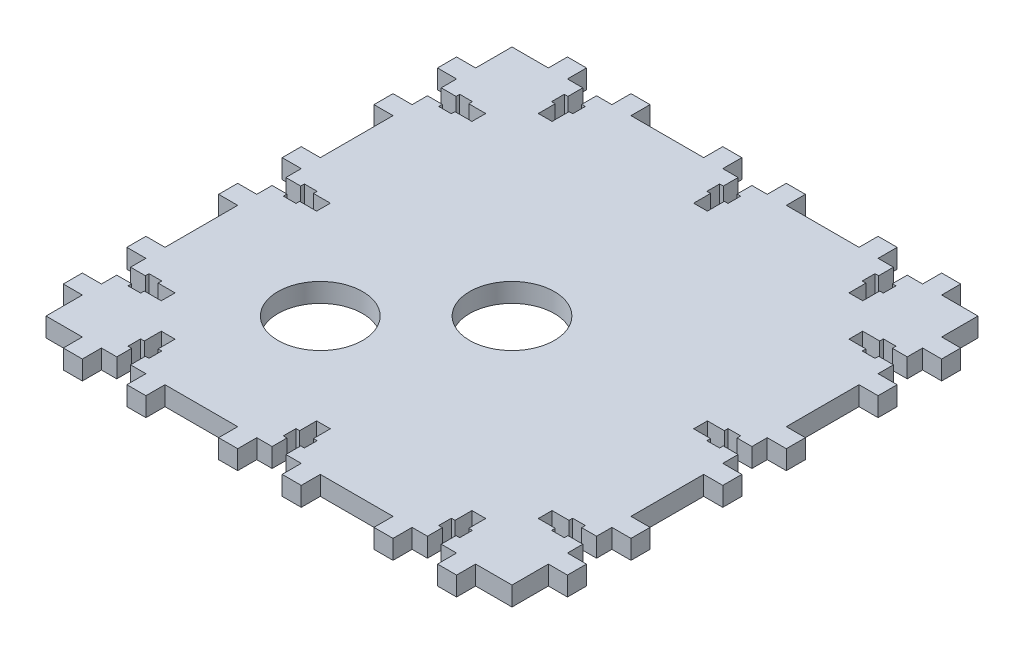
SolidWorks part; units mm, degrees
ref_plane "Front Plane" through (0, 0, 0) normal (0, 0, 1) x (1, 0, 0)
ref_plane "Top Plane" through (0, 0, 0) normal (0, 1, 0) x (1, 0, 0)
ref_plane "Right Plane" through (0, 0, 0) normal (1, 0, 0) x (0, 0, -1)
sketch "Sketch1" plane through (0, 0, 0) normal (0, 1, 0) x (1, 0, 0)
  line L0 (0, 0) -> (0, -110) construction
  line L1 (-110, -110) -> (110, -110)
  line L2 (-110, -110) -> (-110, 110)
  line L3 (-110, 110) -> (110, 110)
  line L4 (110, -110) -> (110, 110)
  line L5 (-110, -110) -> (110, 110) construction
  line L6 (-110, 110) -> (110, -110) construction
  line L7 (0, 0) -> (110, 0) construction
  line L8 (110, -32) -> (-110, -32) construction
  line L9 (-110, 72.5) -> (110, 72.5) construction
  circle A0 centre (0, 0) radius 20
  circle A6 centre (-45.2548, -45.2548) radius 20
  point P0 (0, 0)
  point P28 (0, 0)
  line B0 (-92.8333, -110) -> (-92.8333, -119)
  line B1 (-92.8333, -119) -> (-83.8333, -119)
  line B2 (-83.8333, -119) -> (-83.8333, -110)
  line B3 (-83.8333, -110) -> (-76.5833, -110)
  line B4 (-76.5833, -110) -> (-76.5833, -103)
  line B5 (-76.5833, -103) -> (-78.3083, -103)
  line B6 (-78.3083, -103) -> (-78.3083, -97)
  line B7 (-78.3083, -97) -> (-76.5833, -97)
  line B8 (-76.5833, -97) -> (-76.5833, -89)
  line B9 (-76.5833, -89) -> (-70.0833, -89)
  line B10 (-73.3333, -89) -> (-73.3333, -110) construction
  line B11 (-70.0833, -97) -> (-70.0833, -89)
  line B12 (-68.3583, -97) -> (-70.0833, -97)
  line B13 (-68.3583, -103) -> (-68.3583, -97)
  line B14 (-70.0833, -103) -> (-68.3583, -103)
  line B15 (-70.0833, -110) -> (-70.0833, -103)
  line B16 (-62.8333, -110) -> (-70.0833, -110)
  line B17 (-62.8333, -119) -> (-62.8333, -110)
  line B18 (-53.8333, -119) -> (-62.8333, -119)
  line B19 (-53.8333, -110) -> (-53.8333, -119)
  line B20 (-19.5, -110) -> (-19.5, -119)
  line B21 (-19.5, -119) -> (-10.5, -119)
  line B22 (-10.5, -119) -> (-10.5, -110)
  line B23 (-10.5, -110) -> (-3.25, -110)
  line B24 (-3.25, -110) -> (-3.25, -103)
  line B25 (-3.25, -103) -> (-4.975, -103)
  line B26 (-4.975, -103) -> (-4.975, -97)
  line B27 (-4.975, -97) -> (-3.25, -97)
  line B28 (-3.25, -97) -> (-3.25, -89)
  line B29 (-3.25, -89) -> (3.25, -89)
  line B30 (0, -89) -> (0, -110) construction
  line B31 (3.25, -97) -> (3.25, -89)
  line B32 (4.975, -97) -> (3.25, -97)
  line B33 (4.975, -103) -> (4.975, -97)
  line B34 (3.25, -103) -> (4.975, -103)
  line B35 (3.25, -110) -> (3.25, -103)
  line B36 (10.5, -110) -> (3.25, -110)
  line B37 (10.5, -119) -> (10.5, -110)
  line B38 (19.5, -119) -> (10.5, -119)
  line B39 (19.5, -110) -> (19.5, -119)
  line B40 (53.8333, -110) -> (53.8333, -119)
  line B41 (53.8333, -119) -> (62.8333, -119)
  line B42 (62.8333, -119) -> (62.8333, -110)
  line B43 (62.8333, -110) -> (70.0833, -110)
  line B44 (70.0833, -110) -> (70.0833, -103)
  line B45 (70.0833, -103) -> (68.3583, -103)
  line B46 (68.3583, -103) -> (68.3583, -97)
  line B47 (68.3583, -97) -> (70.0833, -97)
  line B48 (70.0833, -97) -> (70.0833, -89)
  line B49 (70.0833, -89) -> (76.5833, -89)
  line B50 (73.3333, -89) -> (73.3333, -110) construction
  line B51 (76.5833, -97) -> (76.5833, -89)
  line B52 (78.3083, -97) -> (76.5833, -97)
  line B53 (78.3083, -103) -> (78.3083, -97)
  line B54 (76.5833, -103) -> (78.3083, -103)
  line B55 (76.5833, -110) -> (76.5833, -103)
  line B56 (83.8333, -110) -> (76.5833, -110)
  line B57 (83.8333, -119) -> (83.8333, -110)
  line B58 (92.8333, -119) -> (83.8333, -119)
  line B59 (92.8333, -110) -> (92.8333, -119)
  line B60 (-110, 92.8333) -> (-119, 92.8333)
  line B61 (-119, 92.8333) -> (-119, 83.8333)
  line B62 (-119, 83.8333) -> (-110, 83.8333)
  line B63 (-110, 83.8333) -> (-110, 76.5833)
  line B64 (-110, 76.5833) -> (-103, 76.5833)
  line B65 (-103, 76.5833) -> (-103, 78.3083)
  line B66 (-103, 78.3083) -> (-97, 78.3083)
  line B67 (-97, 78.3083) -> (-97, 76.5833)
  line B68 (-97, 76.5833) -> (-89, 76.5833)
  line B69 (-89, 76.5833) -> (-89, 70.0833)
  line B70 (-89, 73.3333) -> (-110, 73.3333) construction
  line B71 (-97, 70.0833) -> (-89, 70.0833)
  line B72 (-97, 68.3583) -> (-97, 70.0833)
  line B73 (-103, 68.3583) -> (-97, 68.3583)
  line B74 (-103, 70.0833) -> (-103, 68.3583)
  line B75 (-110, 70.0833) -> (-103, 70.0833)
  line B76 (-110, 62.8333) -> (-110, 70.0833)
  line B77 (-119, 62.8333) -> (-110, 62.8333)
  line B78 (-119, 53.8333) -> (-119, 62.8333)
  line B79 (-110, 53.8333) -> (-119, 53.8333)
  line B80 (-110, 19.5) -> (-119, 19.5)
  line B81 (-119, 19.5) -> (-119, 10.5)
  line B82 (-119, 10.5) -> (-110, 10.5)
  line B83 (-110, 10.5) -> (-110, 3.25)
  line B84 (-110, 3.25) -> (-103, 3.25)
  line B85 (-103, 3.25) -> (-103, 4.975)
  line B86 (-103, 4.975) -> (-97, 4.975)
  line B87 (-97, 4.975) -> (-97, 3.25)
  line B88 (-97, 3.25) -> (-89, 3.25)
  line B89 (-89, 3.25) -> (-89, -3.25)
  line B90 (-89, 0) -> (-110, 0) construction
  line B91 (-97, -3.25) -> (-89, -3.25)
  line B92 (-97, -4.975) -> (-97, -3.25)
  line B93 (-103, -4.975) -> (-97, -4.975)
  line B94 (-103, -3.25) -> (-103, -4.975)
  line B95 (-110, -3.25) -> (-103, -3.25)
  line B96 (-110, -10.5) -> (-110, -3.25)
  line B97 (-119, -10.5) -> (-110, -10.5)
  line B98 (-119, -19.5) -> (-119, -10.5)
  line B99 (-110, -19.5) -> (-119, -19.5)
  line B100 (-110, -53.8333) -> (-119, -53.8333)
  line B101 (-119, -53.8333) -> (-119, -62.8333)
  line B102 (-119, -62.8333) -> (-110, -62.8333)
  line B103 (-110, -62.8333) -> (-110, -70.0833)
  line B104 (-110, -70.0833) -> (-103, -70.0833)
  line B105 (-103, -70.0833) -> (-103, -68.3583)
  line B106 (-103, -68.3583) -> (-97, -68.3583)
  line B107 (-97, -68.3583) -> (-97, -70.0833)
  line B108 (-97, -70.0833) -> (-89, -70.0833)
  line B109 (-89, -70.0833) -> (-89, -76.5833)
  line B110 (-89, -73.3333) -> (-110, -73.3333) construction
  line B111 (-97, -76.5833) -> (-89, -76.5833)
  line B112 (-97, -78.3083) -> (-97, -76.5833)
  line B113 (-103, -78.3083) -> (-97, -78.3083)
  line B114 (-103, -76.5833) -> (-103, -78.3083)
  line B115 (-110, -76.5833) -> (-103, -76.5833)
  line B116 (-110, -83.8333) -> (-110, -76.5833)
  line B117 (-119, -83.8333) -> (-110, -83.8333)
  line B118 (-119, -92.8333) -> (-119, -83.8333)
  line B119 (-110, -92.8333) -> (-119, -92.8333)
  line B120 (92.8333, 110) -> (92.8333, 119)
  line B121 (92.8333, 119) -> (83.8333, 119)
  line B122 (83.8333, 119) -> (83.8333, 110)
  line B123 (83.8333, 110) -> (76.5833, 110)
  line B124 (76.5833, 110) -> (76.5833, 103)
  line B125 (76.5833, 103) -> (78.3083, 103)
  line B126 (78.3083, 103) -> (78.3083, 97)
  line B127 (78.3083, 97) -> (76.5833, 97)
  line B128 (76.5833, 97) -> (76.5833, 89)
  line B129 (76.5833, 89) -> (70.0833, 89)
  line B130 (73.3333, 89) -> (73.3333, 110) construction
  line B131 (70.0833, 97) -> (70.0833, 89)
  line B132 (68.3583, 97) -> (70.0833, 97)
  line B133 (68.3583, 103) -> (68.3583, 97)
  line B134 (70.0833, 103) -> (68.3583, 103)
  line B135 (70.0833, 110) -> (70.0833, 103)
  line B136 (62.8333, 110) -> (70.0833, 110)
  line B137 (62.8333, 119) -> (62.8333, 110)
  line B138 (53.8333, 119) -> (62.8333, 119)
  line B139 (53.8333, 110) -> (53.8333, 119)
  line B140 (19.5, 110) -> (19.5, 119)
  line B141 (19.5, 119) -> (10.5, 119)
  line B142 (10.5, 119) -> (10.5, 110)
  line B143 (10.5, 110) -> (3.25, 110)
  line B144 (3.25, 110) -> (3.25, 103)
  line B145 (3.25, 103) -> (4.975, 103)
  line B146 (4.975, 103) -> (4.975, 97)
  line B147 (4.975, 97) -> (3.25, 97)
  line B148 (3.25, 97) -> (3.25, 89)
  line B149 (3.25, 89) -> (-3.25, 89)
  line B150 (0, 89) -> (0, 110) construction
  line B151 (-3.25, 97) -> (-3.25, 89)
  line B152 (-4.975, 97) -> (-3.25, 97)
  line B153 (-4.975, 103) -> (-4.975, 97)
  line B154 (-3.25, 103) -> (-4.975, 103)
  line B155 (-3.25, 110) -> (-3.25, 103)
  line B156 (-10.5, 110) -> (-3.25, 110)
  line B157 (-10.5, 119) -> (-10.5, 110)
  line B158 (-19.5, 119) -> (-10.5, 119)
  line B159 (-19.5, 110) -> (-19.5, 119)
  line B160 (-53.8333, 110) -> (-53.8333, 119)
  line B161 (-53.8333, 119) -> (-62.8333, 119)
  line B162 (-62.8333, 119) -> (-62.8333, 110)
  line B163 (-62.8333, 110) -> (-70.0833, 110)
  line B164 (-70.0833, 110) -> (-70.0833, 103)
  line B165 (-70.0833, 103) -> (-68.3583, 103)
  line B166 (-68.3583, 103) -> (-68.3583, 97)
  line B167 (-68.3583, 97) -> (-70.0833, 97)
  line B168 (-70.0833, 97) -> (-70.0833, 89)
  line B169 (-70.0833, 89) -> (-76.5833, 89)
  line B170 (-73.3333, 89) -> (-73.3333, 110) construction
  line B171 (-76.5833, 97) -> (-76.5833, 89)
  line B172 (-78.3083, 97) -> (-76.5833, 97)
  line B173 (-78.3083, 103) -> (-78.3083, 97)
  line B174 (-76.5833, 103) -> (-78.3083, 103)
  line B175 (-76.5833, 110) -> (-76.5833, 103)
  line B176 (-83.8333, 110) -> (-76.5833, 110)
  line B177 (-83.8333, 119) -> (-83.8333, 110)
  line B178 (-92.8333, 119) -> (-83.8333, 119)
  line B179 (-92.8333, 110) -> (-92.8333, 119)
  line B180 (110, -92.8333) -> (119, -92.8333)
  line B181 (119, -92.8333) -> (119, -83.8333)
  line B182 (119, -83.8333) -> (110, -83.8333)
  line B183 (110, -83.8333) -> (110, -76.5833)
  line B184 (110, -76.5833) -> (103, -76.5833)
  line B185 (103, -76.5833) -> (103, -78.3083)
  line B186 (103, -78.3083) -> (97, -78.3083)
  line B187 (97, -78.3083) -> (97, -76.5833)
  line B188 (97, -76.5833) -> (89, -76.5833)
  line B189 (89, -76.5833) -> (89, -70.0833)
  line B190 (89, -73.3333) -> (110, -73.3333) construction
  line B191 (97, -70.0833) -> (89, -70.0833)
  line B192 (97, -68.3583) -> (97, -70.0833)
  line B193 (103, -68.3583) -> (97, -68.3583)
  line B194 (103, -70.0833) -> (103, -68.3583)
  line B195 (110, -70.0833) -> (103, -70.0833)
  line B196 (110, -62.8333) -> (110, -70.0833)
  line B197 (119, -62.8333) -> (110, -62.8333)
  line B198 (119, -53.8333) -> (119, -62.8333)
  line B199 (110, -53.8333) -> (119, -53.8333)
  line B200 (110, -19.5) -> (119, -19.5)
  line B201 (119, -19.5) -> (119, -10.5)
  line B202 (119, -10.5) -> (110, -10.5)
  line B203 (110, -10.5) -> (110, -3.25)
  line B204 (110, -3.25) -> (103, -3.25)
  line B205 (103, -3.25) -> (103, -4.975)
  line B206 (103, -4.975) -> (97, -4.975)
  line B207 (97, -4.975) -> (97, -3.25)
  line B208 (97, -3.25) -> (89, -3.25)
  line B209 (89, -3.25) -> (89, 3.25)
  line B210 (89, 0) -> (110, 0) construction
  line B211 (97, 3.25) -> (89, 3.25)
  line B212 (97, 4.975) -> (97, 3.25)
  line B213 (103, 4.975) -> (97, 4.975)
  line B214 (103, 3.25) -> (103, 4.975)
  line B215 (110, 3.25) -> (103, 3.25)
  line B216 (110, 10.5) -> (110, 3.25)
  line B217 (119, 10.5) -> (110, 10.5)
  line B218 (119, 19.5) -> (119, 10.5)
  line B219 (110, 19.5) -> (119, 19.5)
  line B220 (110, 53.8333) -> (119, 53.8333)
  line B221 (119, 53.8333) -> (119, 62.8333)
  line B222 (119, 62.8333) -> (110, 62.8333)
  line B223 (110, 62.8333) -> (110, 70.0833)
  line B224 (110, 70.0833) -> (103, 70.0833)
  line B225 (103, 70.0833) -> (103, 68.3583)
  line B226 (103, 68.3583) -> (97, 68.3583)
  line B227 (97, 68.3583) -> (97, 70.0833)
  line B228 (97, 70.0833) -> (89, 70.0833)
  line B229 (89, 70.0833) -> (89, 76.5833)
  line B230 (89, 73.3333) -> (110, 73.3333) construction
  line B231 (97, 76.5833) -> (89, 76.5833)
  line B232 (97, 78.3083) -> (97, 76.5833)
  line B233 (103, 78.3083) -> (97, 78.3083)
  line B234 (103, 76.5833) -> (103, 78.3083)
  line B235 (110, 76.5833) -> (103, 76.5833)
  line B236 (110, 83.8333) -> (110, 76.5833)
  line B237 (119, 83.8333) -> (110, 83.8333)
  line B238 (119, 92.8333) -> (119, 83.8333)
  line B239 (110, 92.8333) -> (119, 92.8333)
  dimension "D7" = 40
  dimension "D1" = 220
  dimension "D2" = 220
  dimension "D3" = 36.6667
  dimension "D4" = 4
  dimension "D5" = 64
  dimension "D10" = 32
sketch_block_instance "Plot_9mm_M6_bois-1"
sketch_block "Plot_9mm_M6_bois" parameters "D1"=9, "D2"=9, "D3"=16, "D4"=30, "D5"=9.95, "D6"=6.5, "D7"=6, "D8"=8
sketch_block_instance "Plot_9mm_M6_bois-2"
sketch_block_instance "Plot_9mm_M6_bois-3"
sketch_block_instance "Plot_9mm_M6_bois-5"
sketch_block_instance "Plot_9mm_M6_bois-6"
sketch_block_instance "Plot_9mm_M6_bois-7"
sketch_block_instance "Plot_9mm_M6_bois-8"
sketch_block_instance "Plot_9mm_M6_bois-9"
sketch_block_instance "Plot_9mm_M6_bois-10"
sketch_block_instance "Plot_9mm_M6_bois-11"
sketch_block_instance "Plot_9mm_M6_bois-12"
sketch_block_instance "Plot_9mm_M6_bois-13"
extrude "Boss-Extrude1" add sketch "Sketch1" along normal blind 9
sketch "Sketch3" plane through (0, 9, 0) normal (0, 1, 0) x (1, 0, 0)
  line L0 (-110, 44.2946) -> (110, 44.2946) construction
  text T0 "<b>Кирилл</b> <i>2000</i>" font "Century Gothic" height 20
